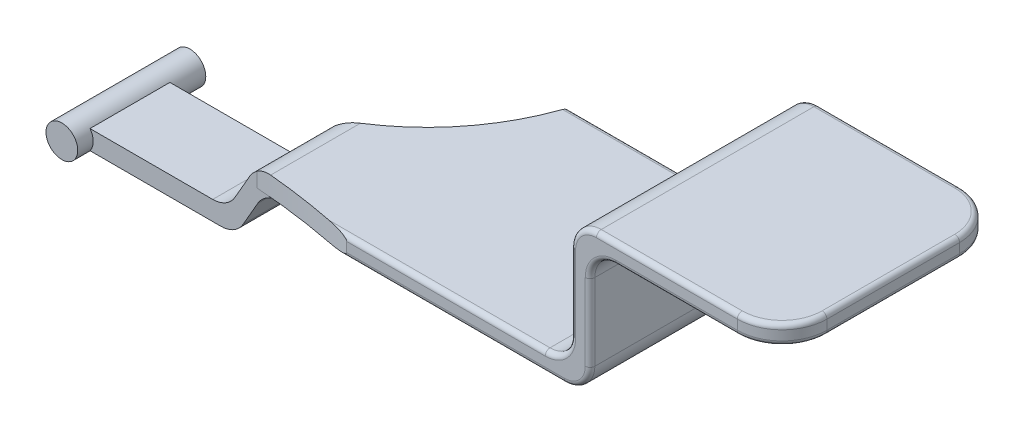
SolidWorks part; units mm, degrees
ref_plane "Front Plane" through (0, 0, 0) normal (0, 0, 1) x (1, 0, 0)
ref_plane "Top Plane" through (0, 0, 0) normal (0, 1, 0) x (1, 0, 0)
ref_plane "Right Plane" through (0, 0, 0) normal (1, 0, 0) x (0, 0, -1)
sketch "Sketch2" plane through (0, 0, 0) normal (0, 0, 1) x (1, 0, 0)
  circle A0 centre (0, 0) radius 2.48
extrude "Boss-Extrude1" add sketch "Sketch2" along normal blind 20
sketch "Sketch3" plane through (0, 0, 0) normal (0, 1, 0) x (1, 0, 0)
  line L1 (0, -5.1) -> (24.73, -5.1)
  line L2 (0, -5.1) -> (0, -17.58)
  line L3 (0, -17.58) -> (24.73, -17.58)
  line L4 (24.73, -5.1) -> (24.73, -17.58)
  dimension "D1" = 12.48
  dimension "D2" = 24.73
extrude "Boss-Extrude3" add sketch "Sketch3" along normal mid plane 3
ref_plane "Plane2" through (0, 0, 5.1) normal (0, 0, 1) x (1, 0, 0)
sketch "Sketch7" plane through (0, 0, 5.1) normal (0, 0, 1) x (1, 0, 0)
  line L0 (21.73, -1.5) -> (24.73, -1.5)
  line L1 (21.73, -1.5) -> (28.062, 9.5)
  line L2 (24.73, -1.5) -> (31.062, 9.5)
  line L3 (28.062, 9.5) -> (31.062, 9.5)
  line L4 (1.9749, -1.5) -> (24.73, -1.5) construction
  dimension "D1" = 11
  dimension "D2" = 3
  dimension "D3" = 2.6
extrude "Boss-Extrude7" add sketch "Sketch7" along normal blind 12.48
ref_plane "Plane3" through (0, 9.5, 0) normal (0, 1, 0) x (1, 0, 0)
sketch "Sketch8" plane through (0, 9.5, 0) normal (0, 1, 0) x (1, 0, 0)
  line L8 (17.5072, -11.34) -> (77.8935, -11.34) construction
  line L9 (72.552, -20.06) -> (44.552, -20.06)
  line L10 (72.552, 14.65) -> (44.552, 14.65)
  line L11 (72.552, -20.06) -> (72.552, 14.65)
  line L12 (28.062, -5.1) -> (28.062, -17.58)
  arc A2 (44.552, -20.06) -> (28.062, -17.58) centre (20.7967, -121.951) ccw
  arc A3 (28.062, -5.1) -> (44.552, 14.65) centre (11.7781, 25.2551) ccw
  dimension "D5" = 12.48
extrude "Boss-Extrude9" add sketch "Sketch8" against normal blind 3
ref_plane "Plane4" through (0, 0, 20.06) normal (0, 0, 1) x (1, 0, 0)
sketch "Sketch9" plane through (0, 0, 20.06) normal (0, 0, 1) x (1, 0, 0)
  line L1 (72.552, 9.5) -> (82.552, 9.5)
  line L2 (72.552, 9.5) -> (72.552, 6.5)
  line L3 (72.552, 6.5) -> (82.552, 6.5)
  line L4 (82.552, 9.5) -> (82.552, 6.5)
  dimension "D1" = 3
  dimension "D2" = 10
extrude "Boss-Extrude10" add sketch "Sketch9" against normal blind 34.71
sketch "Sketch10" plane through (0, 0, 20.06) normal (0, 0, 1) x (1, 0, 0)
  line L1 (82.552, 6.5) -> (79.552, 6.5)
  line L2 (82.552, 6.5) -> (82.552, 29.5)
  line L3 (82.552, 29.5) -> (79.552, 29.5)
  line L4 (79.552, 6.5) -> (79.552, 29.5)
  dimension "D1" = 3
  dimension "D2" = 23
extrude "Boss-Extrude11" add sketch "Sketch10" against normal blind 34.71
sketch "Sketch11" plane through (82.552, 0, 0) normal (1, 0, 0) x (0, 0, -1)
  line L0 (14.65, 6.5) -> (14.65, 29.5) construction
  line L1 (-20.06, 29.5) -> (14.65, 29.5)
  line L2 (-20.06, 29.5) -> (-20.06, 26.5)
  line L3 (-20.06, 26.5) -> (14.65, 26.5)
  line L4 (14.65, 29.5) -> (14.65, 26.5)
  dimension "D1" = 3
extrude "Boss-Extrude12" add sketch "Sketch11" along normal blind 30
fillet "Fillet1" radius 4 8 edges at (28.062, 9.5, 11.34) (23.4569, 1.5, 11.34) (24.73, -1.5, 11.34) (29.3351, 6.5, 11.34) (82.552, 6.5, 2.705) (79.552, 9.5, 2.705) (79.552, 29.5, 2.705) (82.552, 26.5, 2.705)
fillet "Fillet3" radius 7 2 edges at (112.552, 28, 20.06) (112.552, 28, -14.65)
fillet "Fillet4" radius 0.75 27 edges at (61.552, 6.5, 20.06) (81.3805, 7.6716, 20.06) (82.552, 16.5, 20.06) (82.552, 16.5, -14.65) (83.7236, 25.3284, 20.06) (96.052, 26.5, 20.06) (110.5018, 26.5, 18.0097) (112.552, 26.5, 2.705) (110.5018, 26.5, -12.5997) (60.052, 9.5, 20.06) (78.3805, 10.6716, 20.06) (79.552, 19.5, -14.65) (79.552, 19.5, 20.06) (80.7236, 28.3284, 20.06) (94.552, 29.5, 20.06) (110.5018, 29.5, 18.0097) (112.552, 29.5, 2.705) (110.5018, 29.5, -12.5997) (80.7236, 28.3284, -14.65) (78.3805, 10.6716, -14.65) (60.052, 9.5, -14.65) (44.552, 8, -14.65) (61.552, 6.5, -14.65) (81.3805, 7.6716, -14.65) (83.7236, 25.3284, -14.65) (96.052, 26.5, -14.65) (94.552, 29.5, -14.65)
ref_plane "Plane5" through (119.8511, 0, 0) normal (1, 0, 0) x (0, 0, -1)
mirror "Mirror5" about plane through (119.8511, 0, 0) normal (1, 0, 0) of bodies 112
delete or keep bodies "Body-Delete/Keep 1" type delete bodies bodies 112
mirror "Mirror6" about plane through (119.8511, 0, 0) normal (1, 0, 0) of bodies 113
delete or keep bodies "Body-Delete/Keep 2" type delete bodies bodies 113
